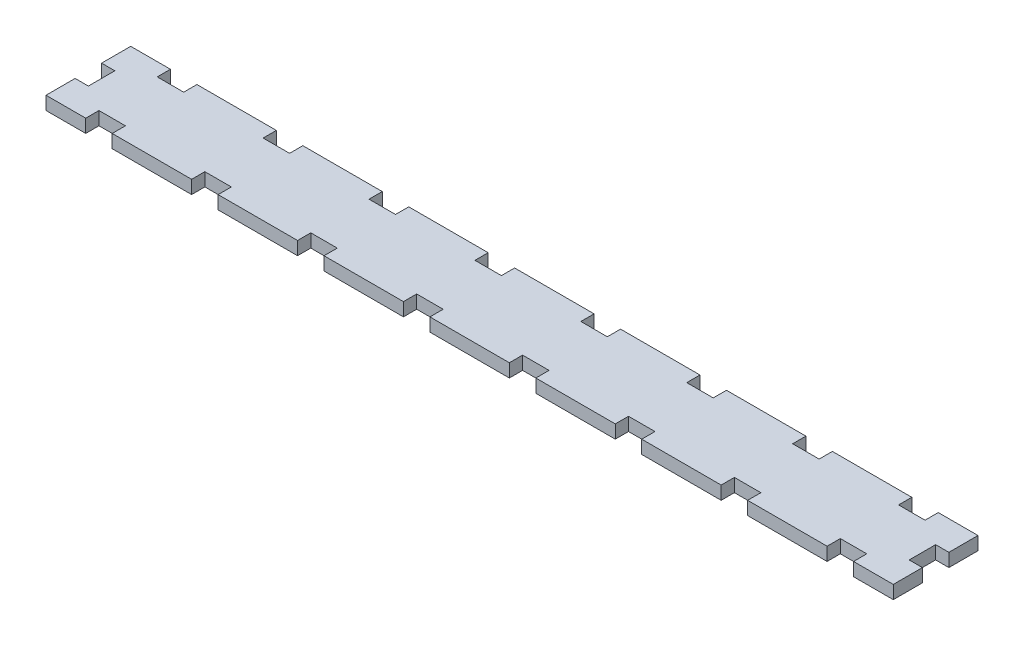
SolidWorks part; units mm, degrees
ref_plane "Front Plane" through (0, 0, 0) normal (0, 0, 1) x (1, 0, 0)
ref_plane "Top Plane" through (0, 0, 0) normal (0, 1, 0) x (1, 0, 0)
ref_plane "Right Plane" through (0, 0, 0) normal (1, 0, 0) x (0, 0, -1)
sketch "Sketch1" plane through (0, 0, 0) normal (0, 1, 0) x (1, 0, 0)
  line L1 (-101.6, 10.16) -> (101.6, 10.16)
  line L2 (-101.6, 10.16) -> (-101.6, -10.16)
  line L3 (-101.6, -10.16) -> (101.6, -10.16)
  line L4 (101.6, 10.16) -> (101.6, -10.16)
  line L5 (-101.6, 10.16) -> (101.6, -10.16) construction
  line L6 (-101.6, -10.16) -> (101.6, 10.16) construction
  point P0 (0, 0)
  dimension "D1" = 20.32
  dimension "D2" = 203.2
extrude "Boss-Extrude1" add sketch "Sketch1" along normal blind 3.175
sketch "Sketch2" plane through (0, 3.175, 0) normal (0, 1, 0) x (1, 0, 0)
  line L0 (101.6, 10.16) -> (-101.6, 10.16) construction
  line L1 (92.075, 10.16) -> (85.725, 10.16)
  line L2 (92.075, 10.16) -> (92.075, 6.985)
  line L3 (92.075, 6.985) -> (85.725, 6.985)
  line L4 (85.725, 10.16) -> (85.725, 6.985)
  line L5 (101.6, -10.16) -> (101.6, 10.16) construction
  dimension "D1" = 3.175
  dimension "D2" = 6.35
  dimension "D3" = 9.525
extrude "Cut-Extrude1" cut sketch "Sketch2" against normal through all
pattern_linear "LPattern1" count 8 spacing 25.4 along (-1, 0, 0) of "Cut-Extrude1"
mirror "Mirror1" about plane through (0, 0, 0) normal (0, 0, 1) of "LPattern1", "Cut-Extrude1"
sketch "Sketch3" plane through (0, 3.175, 0) normal (0, 1, 0) x (1, 0, 0)
  line L0 (101.6, -10.16) -> (101.6, 10.16) construction
  line L1 (104.775, 3.175) -> (98.425, 3.175)
  line L2 (104.775, 3.175) -> (104.775, -3.175)
  line L3 (104.775, -3.175) -> (98.425, -3.175)
  line L4 (98.425, 3.175) -> (98.425, -3.175)
  line L5 (104.775, 3.175) -> (98.425, -3.175) construction
  line L6 (104.775, -3.175) -> (98.425, 3.175) construction
  line L7 (-101.6, 10.16) -> (-101.6, -10.16) construction
  line L8 (-104.775, 3.175) -> (-98.425, 3.175)
  line L9 (-104.775, 3.175) -> (-104.775, -3.175)
  line L10 (-104.775, -3.175) -> (-98.425, -3.175)
  line L11 (-98.425, 3.175) -> (-98.425, -3.175)
  line L12 (-104.775, 3.175) -> (-98.425, -3.175) construction
  line L13 (-104.775, -3.175) -> (-98.425, 3.175) construction
  point P0 (101.6, 0)
  point P7 (-101.6, 0)
  dimension "D1" = 6.35
  dimension "D2" = 6.35
extrude "Cut-Extrude2" cut sketch "Sketch3" against normal through all
